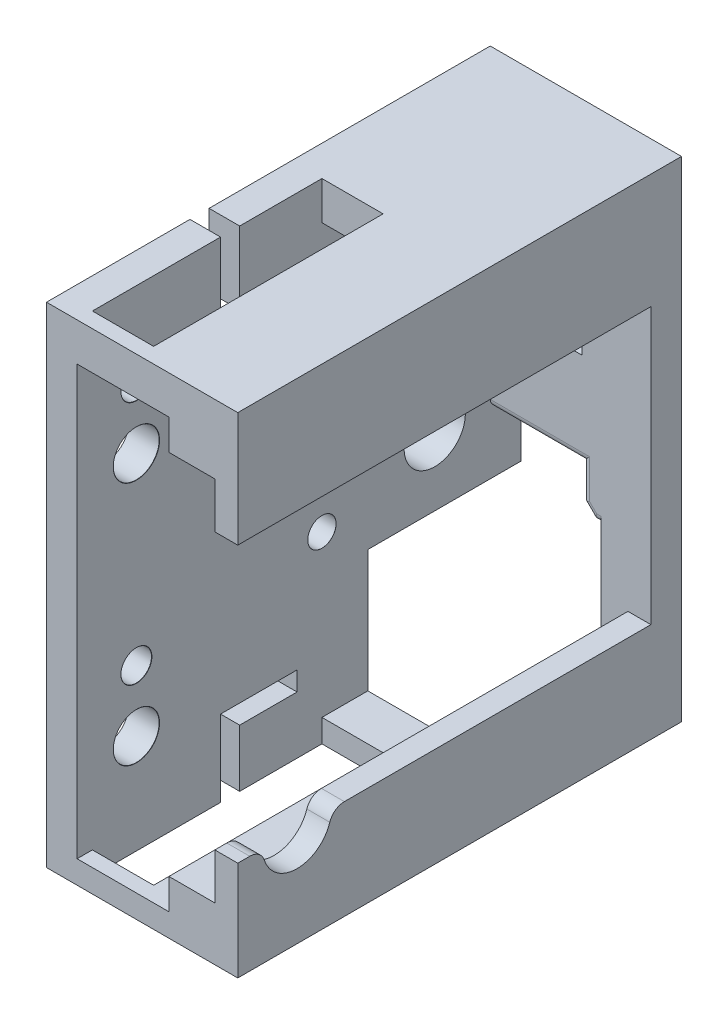
SolidWorks part; units mm, degrees
ref_plane "Front Plane" through (0, 0, 0) normal (1, 0, 0) x (0, 1, 0)
ref_plane "Top Plane" through (0, 0, 0) normal (0, 0, 1) x (0, 1, 0)
ref_plane "Right Plane" through (0, 0, 0) normal (0, 1, 0) x (-1, 0, 0)
sketch "Sketch1" plane through (0, 0, 0) normal (1, 0, 0) x (0, 1, 0)
  line L0 (-18, 21.25) -> (14, 21.25) construction
  line L1 (-31, 29) -> (31, 29)
  line L2 (-31, 29) -> (-31, -29)
  line L3 (-31, -29) -> (31, -29)
  line L4 (31, 29) -> (31, -29)
  line L5 (-31, 29) -> (31, -29) construction
  line L6 (-31, -29) -> (31, 29) construction
  line L7 (7, -16) -> (7, -3) construction
  line L8 (-7, -3) -> (7, -3) construction
  line L9 (0, -14.85) -> (0, 14.85) construction
  point P0 (0, 0)
  point P6 (-18, 21.25)
  point P7 (14, 21.25)
  point P10 (7, -3)
  point P14 (-7, -3)
  point P16 (-3, -17.75)
  point P17 (7, -16)
  dimension "D1" = 62
  dimension "D2" = 58
  dimension "D3" = 32
  dimension "D4" = 18
  dimension "D5" = 7.75
  dimension "D6" = 14
  dimension "D7" = 26
  dimension "D8" = 3
  dimension "D9" = 39
  dimension "D10" = 7
  dimension "D11" = 13
extrude "Boss-Extrude1" add sketch "Sketch1" against normal blind 4
sketch "Sketch3" plane through (0, 0, 29) normal (0, 0, 1) x (1, 0, 0)
  line L0 (0, -31.9) -> (0, 31.9) construction
  line L1 (0, 31) -> (21, 31)
  line L2 (0, 31) -> (0, 28)
  line L3 (0, 28) -> (18, 28)
  line L4 (21, 31) -> (21, 28)
  line L5 (-4, 31) -> (0, 31) construction
  line L6 (14.85, 0) -> (-14.85, 0) construction
  line L7 (18, 28) -> (21, 28) construction
  line L8 (18, 28) -> (18, 18)
  line L9 (18, 18) -> (21, 18)
  line L10 (21, 28) -> (21, 18)
  line L11 (0, -31) -> (21, -31)
  line L12 (21, -31) -> (21, -28)
  line L13 (21, -28) -> (21, -18)
  line L14 (18, -18) -> (21, -18)
  line L15 (18, -28) -> (18, -18)
  line L16 (0, -28) -> (18, -28)
  line L17 (0, -31) -> (0, -28)
  dimension "D1" = 3
  dimension "D2" = 3
  dimension "D3" = 18
  dimension "D4" = 10
extrude "Boss-Extrude2" add sketch "Sketch3" against normal blind 58
hole_wizard "Ø4.0mm Dowel Hole1" positions "Sketch4" profile "Sketch5" hole size "Ø4.0" standard "DIN"
sketch "Sketch4" plane through (0, 0, 0) normal (1, 0, 0) x (0, 0, -1)
  point P0 (3, -7)
  point P3 (3, 7)
  point P6 (16, 7)
sketch "Sketch5" plane through (0, -7, -3) normal (0, 1, 0) x (0, 0, -1)
  line L0 (0, 0) -> (0, 31.1116)
  line L1 (0, 31.1116) -> (1.85, 30)
  line L2 (1.85, 30) -> (1.85, 0.005)
  line L3 (1.85, 0.005) -> (1.855, 0)
  line L5 (1.855, 0) -> (0, 0)
  line L6 (-1.85, 0.005) -> (-1.855, 0) construction
  line L10 (0, 31.1116) -> (-1.85, 30) construction
  line L11 (0, -6.35) -> (0, 107.95) construction
  dimension "Hole Dia." = 3.7
  dimension "Hole Depth" = 30
  dimension "Near C'Sink Dia." = 3.71
  dimension "Near C'Sink Angle" = 90
  dimension "Drill Angle" = 118
hole_wizard "Ø6.0mm Dowel Hole1" positions "Sketch6" profile "Sketch7" hole size "Ø6.0" standard "DIN"
sketch "Sketch6" plane through (0, 0, 0) normal (1, 0, 0) x (0, 0, -1)
  point P0 (-21.25, 14)
  point P3 (-21.25, -18)
  point P6 (17.75, -3)
sketch "Sketch7" plane through (0, 14, 21.25) normal (0, 1, 0) x (0, 0, -1)
  line L0 (0, 0) -> (0, 31.8026)
  line L1 (0, 31.8026) -> (3, 30)
  line L2 (3, 30) -> (3, 0.025)
  line L3 (3, 0.025) -> (3.025, 0)
  line L5 (3.025, 0) -> (0, 0)
  line L6 (-3, 0.025) -> (-3.025, 0) construction
  line L10 (0, 31.8026) -> (-3, 30) construction
  line L11 (0, -6.35) -> (0, 107.95) construction
  dimension "Hole Dia." = 6
  dimension "Hole Depth" = 30
  dimension "Near C'Sink Dia." = 6.05
  dimension "Near C'Sink Angle" = 90
  dimension "Drill Angle" = 118
sketch "Sketch9" plane through (0, 0, -29) normal (0, 0, -1) x (1, 0, 0)
  line L5 (-4, -31) -> (21, -31) construction
  line L6 (21, 31) -> (12, 31)
  line L7 (21, 31) -> (21, -31)
  line L8 (21, -31) -> (12, -31)
  line L9 (12, 31) -> (12, -31)
  line L10 (18, 18) -> (18, 28) construction
  dimension "D1" = 6
extrude "Boss-Extrude3" add sketch "Sketch9" against normal blind 4
sketch "Sketch11" plane through (0, -28, 0) normal (0, 1, 0) x (-1, 0, 0)
  line L0 (4, -29) -> (-21, -29) construction
  line L1 (-12, -29) -> (-21, -29)
  line L2 (-12, -29) -> (-12, 29)
  line L3 (-12, 29) -> (-21, 29)
  line L4 (-21, -29) -> (-21, 29)
  line L5 (4, -29) -> (4, 29) construction
  dimension "D1" = 16
extrude "Boss-Extrude4" add sketch "Sketch11" along normal blind 4
mirror "Mirror1" about plane through (0, 0, 0) normal (0, 1, 0) of "Boss-Extrude4"
sketch "Sketch12" plane through (0, 0, 0) normal (1, 0, 0) x (0, 1, 0)
  line L0 (-18, 21.25) -> (14, 21.25) construction
  line L1 (-10, 21.25) -> (22, 21.25) construction
  point P0 (-10, 21.25)
  point P1 (22, 21.25)
  dimension "D1" = 32
  dimension "D2" = 8
hole_wizard "Ø4.0mm Dowel Hole2" positions "Sketch13" profile "Sketch14" hole size "Ø4.0" standard "DIN"
sketch "Sketch13" plane through (0, 0, 0) normal (1, 0, 0) x (0, 0, -1)
  point P0 (-21.25, -10)
  point P3 (-21.25, 22)
sketch "Sketch14" plane through (0, -10, 21.25) normal (0, 1, 0) x (0, 0, -1)
  line L0 (0, 0) -> (0, 31.2017)
  line L1 (0, 31.2017) -> (2, 30)
  line L2 (2, 30) -> (2, 0.025)
  line L3 (2, 0.025) -> (2.025, 0)
  line L5 (2.025, 0) -> (0, 0)
  line L6 (-2, 0.025) -> (-2.025, 0) construction
  line L10 (0, 31.2017) -> (-2, 30) construction
  line L11 (0, -6.35) -> (0, 107.95) construction
  dimension "Hole Dia." = 4
  dimension "Hole Depth" = 30
  dimension "Near C'Sink Dia." = 4.05
  dimension "Near C'Sink Angle" = 90
  dimension "Drill Angle" = 118
sketch "Sketch17" plane through (0, -31, 0) normal (0, -1, 0) x (1, 0, 0)
  line L0 (0, -31.9) -> (0, 31.9) construction
  line L1 (0, 27) -> (8, 27)
  line L2 (0, 27) -> (0, -3)
  line L3 (0, -3) -> (8, -3)
  line L4 (8, 27) -> (8, -3)
  line L6 (-4, 29) -> (21, 29) construction
  dimension "D1" = 8
  dimension "D2" = 2
  dimension "D3" = 30
extrude "Cut-Extrude1" cut sketch "Sketch17" against normal blind 10
sketch "Sketch20" plane through (0, 0, 0) normal (1, 0, 0) x (0, 1, 0)
  line L1 (-28, -9) -> (-12, -9)
  line L2 (-28, -9) -> (-28, -29)
  line L3 (-28, -29) -> (-12, -29)
  line L4 (-12, -9) -> (-12, -29)
  line L5 (-28, 27) -> (-28, 29) construction
  line L6 (-31, -29) -> (31, -29) construction
  dimension "D1" = 20
  dimension "D2" = 16
extrude "Cut-Extrude2" cut sketch "Sketch20" against normal blind 10
sketch "Sketch21" plane through (0, 0, 0) normal (1, 0, 0) x (0, 1, 0)
  line L0 (-31, -29) -> (-31, 29) construction
  line L1 (-31, 10.25) -> (-21, 10.25)
  line L2 (-31, 10.25) -> (-31, 7.75)
  line L3 (-31, 7.75) -> (-21, 7.75) construction
  line L4 (-21, 10.25) -> (-21, 7.75)
  line L5 (-31, 7.75) -> (-23.5, 7.75)
  line L6 (-21, 7.75) -> (-23.5, 7.75) construction
  line L7 (-21, 7.75) -> (-21, 0.25)
  line L8 (-21, 0.25) -> (-23.5, 0.25)
  line L9 (-23.5, 7.75) -> (-23.5, 0.25)
  point P6 (-18, 21.25)
  dimension "D1" = 11
  dimension "D2" = 2.5
  dimension "D3" = 3
  dimension "D4" = 2.5
  dimension "D5" = 7.5
extrude "Cut-Extrude3" cut sketch "Sketch21" against normal blind 10
mirror "Mirror2" about plane through (0, 0, 0) normal (0, 1, 0) of "Cut-Extrude1", "Cut-Extrude3"
sketch "Sketch22" plane through (0, 0, 0) normal (1, 0, 0) x (0, 1, 0)
  circle A0 centre (-3, -17.75) radius 4
  circle A1 centre (-3, -17.75) radius 3.025 construction
  dimension "D1" = 8
extrude "Cut-Extrude4" cut sketch "Sketch22" against normal blind 10
sketch "Sketch23" plane through (0, -31, 0) normal (0, -1, 0) x (1, 0, 0)
  line L0 (-4, 7.75) -> (-4, -29) construction
  line L1 (-4, -9) -> (8, -9)
  line L2 (-4, -9) -> (-4, -29)
  line L3 (-4, -29) -> (8, -29)
  line L4 (8, -9) -> (8, -29)
  line L5 (-4, -29) -> (21, -29) construction
  line L6 (8, -3) -> (8, 27) construction
extrude "Cut-Extrude5" cut sketch "Sketch23" against normal blind 10
sketch "Sketch24" plane through (0, 0, -25) normal (0, 0, 1) x (1, 0, 0)
  line L0 (12, -24) -> (18, -24) construction
  line L1 (12, -24) -> (14.5, -24)
  line L2 (12, -24) -> (12, -10)
  line L3 (12, -10) -> (14.5, -10)
  line L4 (14.5, -24) -> (14.5, -10)
  dimension "D1" = 2.5
  dimension "D2" = 14
extrude "Cut-Extrude6" cut sketch "Sketch24" against normal blind 10
other "Move Face1" face at (4.1429, -31, 4.7143) parameters "D1"=0.5
other "Move Face2" face at (3.5, 31, 7) parameters "D1"=2
sketch "Sketch25" plane through (0, 0, -25) normal (0, 0, 1) x (1, 0, 0)
  line L0 (12, -10) -> (12, 24) construction
  line L1 (12, -4) -> (0, -4)
  line L2 (12, -4) -> (12, 8)
  line L3 (12, 8) -> (0, 8)
  line L4 (0, -4) -> (0, 8)
  line L5 (0, -31.9) -> (0, 31.9) construction
  line L6 (14.85, 0) -> (-14.85, 0) construction
  dimension "D1" = 12
  dimension "D2" = 8
extrude "Boss-Extrude5" add sketch "Sketch25" against normal blind 4
sketch "Sketch26" plane through (-4, 0, 0) normal (-1, 0, 0) x (0, -1, 0)
  line L2 (6.0022, -22.95) -> (9.0044, -17.75)
  line L3 (9.0044, -17.75) -> (6.0022, -12.55)
  line L4 (6.0022, -12.55) -> (-0.0022, -12.55)
  line L5 (-0.0022, -12.55) -> (-3.0044, -17.75)
  line L6 (-3.0044, -17.75) -> (-0.0022, -22.95)
  line L7 (-0.0022, -22.95) -> (6.0022, -22.95)
  circle A0 centre (3, -17.75) radius 5.2 construction
  dimension "D1" = 10.4
extrude "Extrude-Thin1" add sketch "Sketch26" along normal blind 2 thin
chamfer "Chamfer1" distance 1.5 angle 45 1 edges at (12, -10, -27)
fillet "Fillet3" radius 1 4 edges at (6, -4, -25) (14, -10, -25) (12.75, -9.25, -25) (12, -6.25, -25)
sketch "Sketch28" plane through (21, 0, 0) normal (1, 0, 0) x (0, 1, 0)
  circle A0 centre (-18, 21.25) radius 4.5
  dimension "D1" = 9
extrude "Cut-Extrude7" cut sketch "Sketch28" against normal blind 10
fillet "Fillet4" radius 2 2 edges at (19.5, -18, 25.75) (19.5, -18, 16.75)
sketch "Sketch29" plane through (-4, 0, 0) normal (-1, 0, 0) x (0, -1, 0)
  line L1 (-5.3834, -5.8) -> (-3.7668, -3)
  line L2 (-3.7668, -3) -> (-5.3834, -0.2)
  line L3 (-5.3834, -0.2) -> (-8.6166, -0.2)
  line L4 (-8.6166, -0.2) -> (-10.2332, -3)
  line L5 (-10.2332, -3) -> (-8.6166, -5.8)
  line L6 (-8.6166, -5.8) -> (-5.3834, -5.8)
  line L7 (8.6166, -5.8) -> (10.2332, -3)
  line L8 (10.2332, -3) -> (8.6166, -0.2)
  line L9 (8.6166, -0.2) -> (5.3834, -0.2)
  line L10 (5.3834, -0.2) -> (3.7668, -3)
  line L11 (3.7668, -3) -> (5.3834, -5.8)
  line L12 (5.3834, -5.8) -> (8.6166, -5.8)
  line L13 (-5.3834, -18.8) -> (-3.7668, -16)
  line L14 (-3.7668, -16) -> (-5.3834, -13.2)
  line L15 (-5.3834, -13.2) -> (-8.6166, -13.2)
  line L16 (-8.6166, -13.2) -> (-10.2332, -16)
  line L17 (-10.2332, -16) -> (-8.6166, -18.8)
  line L18 (-8.6166, -18.8) -> (-5.3834, -18.8)
  circle A0 centre (-7, -3) radius 2.8 construction
  circle A1 centre (7, -3) radius 2.8 construction
  circle A2 centre (-7, -16) radius 2.8 construction
  dimension "D1" = 5.6
  dimension "D2" = 5.6
  dimension "D3" = 5.6
extrude "Extrude-Thin2" add sketch "Sketch29" along normal blind 2 thin
sketch "Sketch30" plane through (-4, 0, 0) normal (-1, 0, 0) x (0, -1, 0)
  line L0 (-8.6166, -0.2) -> (-10.2332, -3) construction
  line L1 (-8.6166, -0.2) -> (-10.2332, -3)
  line L2 (5.3834, -0.2) -> (3.7668, -3) construction
  line L3 (8.6166, -0.2) -> (5.3834, -0.2) construction
  line L4 (10.2332, -3) -> (8.6166, -0.2) construction
  line L5 (8.6166, -5.8) -> (10.2332, -3) construction
  line L6 (5.3834, -5.8) -> (8.6166, -5.8) construction
  line L7 (3.7668, -3) -> (5.3834, -5.8) construction
  line L8 (-10.2332, -3) -> (-8.6166, -5.8) construction
  line L9 (-8.6166, -5.8) -> (-5.3834, -5.8) construction
  line L10 (-5.3834, -5.8) -> (-3.7668, -3) construction
  line L11 (-3.7668, -3) -> (-5.3834, -0.2) construction
  line L12 (-5.3834, -0.2) -> (-8.6166, -0.2) construction
  line L13 (5.3834, -0.2) -> (3.7668, -3)
  line L14 (8.6166, -0.2) -> (5.3834, -0.2)
  line L15 (10.2332, -3) -> (8.6166, -0.2)
  line L16 (8.6166, -5.8) -> (10.2332, -3)
  line L17 (5.3834, -5.8) -> (8.6166, -5.8)
  line L18 (12, -9) -> (31, -9)
  line L19 (31, -9) -> (31, 7.75)
  line L20 (31, 7.75) -> (23.5, 7.75)
  line L21 (23.5, 7.75) -> (23.5, 0.25)
  line L22 (23.5, 0.25) -> (21, 0.25)
  line L23 (21, 0.25) -> (21, 10.25)
  line L24 (21, 10.25) -> (31, 10.25)
  line L25 (31, 10.25) -> (31, 29)
  line L26 (31, 29) -> (-33, 29)
  line L27 (-33, 29) -> (-33, 10.25)
  line L28 (-33, 10.25) -> (-21, 10.25)
  line L29 (-21, 10.25) -> (-21, 0.25)
  line L30 (-21, 0.25) -> (-23.5, 0.25)
  line L31 (-23.5, 0.25) -> (-23.5, 7.75)
  line L32 (-23.5, 7.75) -> (-33, 7.75)
  line L33 (-33, 7.75) -> (-33, -29)
  line L34 (-33, -29) -> (12, -29)
  line L35 (12, -29) -> (12, -9)
  line L36 (12, -9) -> (31, -9) construction
  line L37 (31, -9) -> (31, 7.75) construction
  line L38 (31, 7.75) -> (23.5, 7.75) construction
  line L39 (23.5, 7.75) -> (23.5, 0.25) construction
  line L40 (23.5, 0.25) -> (21, 0.25) construction
  line L41 (21, 0.25) -> (21, 10.25) construction
  line L42 (21, 10.25) -> (31, 10.25) construction
  line L43 (31, 10.25) -> (31, 29) construction
  line L44 (31, 29) -> (-33, 29) construction
  line L45 (-33, 29) -> (-33, 10.25) construction
  line L46 (-33, 10.25) -> (-21, 10.25) construction
  line L47 (-21, 10.25) -> (-21, 0.25) construction
  line L48 (-21, 0.25) -> (-23.5, 0.25) construction
  line L49 (-23.5, 0.25) -> (-23.5, 7.75) construction
  line L50 (-23.5, 7.75) -> (-33, 7.75) construction
  line L51 (-33, 7.75) -> (-33, -29) construction
  line L52 (-33, -29) -> (12, -29) construction
  line L53 (12, -29) -> (12, -9) construction
  line L54 (3.7668, -3) -> (5.3834, -5.8)
  line L55 (-10.2332, -3) -> (-8.6166, -5.8)
  line L56 (-8.6166, -5.8) -> (-5.3834, -5.8)
  line L57 (-5.3834, -5.8) -> (-3.7668, -3)
  line L58 (-3.7668, -3) -> (-5.3834, -0.2)
  line L59 (-5.3834, -0.2) -> (-8.6166, -0.2)
  line L66 (-10.2332, -16) -> (-8.6166, -18.8)
  line L67 (-8.6166, -18.8) -> (-5.3834, -18.8)
  line L68 (-5.3834, -18.8) -> (-3.7668, -16)
  line L69 (-3.7668, -16) -> (-5.3834, -13.2)
  line L70 (-5.3834, -13.2) -> (-8.6166, -13.2)
  line L71 (-8.6166, -13.2) -> (-10.2332, -16)
  line L72 (-10.2332, -16) -> (-8.6166, -18.8)
  line L73 (-8.6166, -18.8) -> (-5.3834, -18.8)
  line L74 (-5.3834, -18.8) -> (-3.7668, -16)
  line L75 (-3.7668, -16) -> (-5.3834, -13.2)
  line L76 (-5.3834, -13.2) -> (-8.6166, -13.2)
  line L77 (-8.6166, -13.2) -> (-10.2332, -16)
  dimension "D1" = 0
  dimension "D2" = 0
extrude "Cut-Extrude9" cut sketch "Sketch30" against normal blind 0.8
